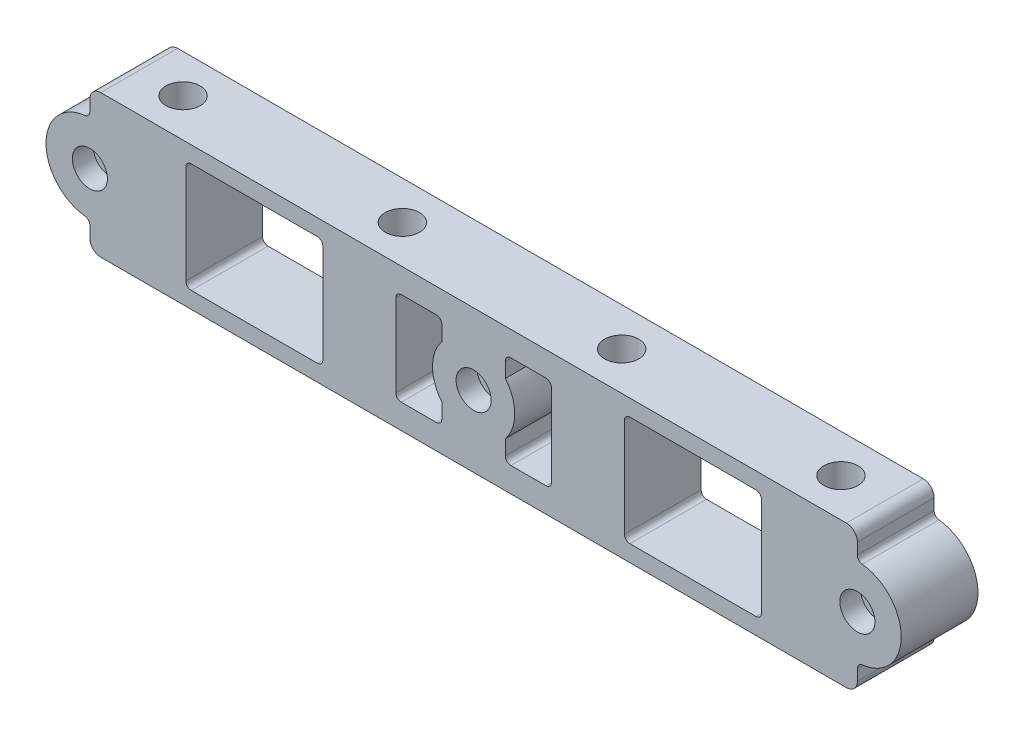
SolidWorks part; units mm, degrees
material "6061-T6 (SS)"
ref_plane "X-Y Datum" through (0, 0, 0) normal (0, 0, 1) x (1, 0, 0)
ref_plane "X-Z Datum" through (0, 0, 0) normal (0, 1, 0) x (1, 0, 0)
ref_plane "Y-Z Datum" through (0, 0, 0) normal (1, 0, 0) x (0, 0, -1)
other "Graphic1"
other "Graphic (Closed) -1"
other "Graphic2"
other "Graphic (Closed) -2"
other "Graphic3"
other "Graphic (Closed) -3"
sketch "Sketch1" plane through (0, 0, 0) normal (0, 1, 0) x (1, 0, 0)
  line L0 (101.6, 8.89) -> (76.2, 8.89) construction
  line L1 (101.6, 17.78) -> (-101.6, 17.78)
  line L2 (101.6, 17.78) -> (101.6, 0)
  line L3 (101.6, 0) -> (-101.6, 0)
  line L4 (-101.6, 17.78) -> (-101.6, 0)
  line L7 (76.2, 8.89) -> (25.4, 8.89) construction
  line L8 (25.4, 8.89) -> (-25.4, 8.89) construction
  line L9 (-25.4, 8.89) -> (-76.2, 8.89) construction
  line L10 (-76.2, 8.89) -> (-101.6, 8.89) construction
  circle A0 centre (76.2, 8.89) radius 3.9688
  circle A1 centre (25.4, 8.89) radius 3.9687
  circle A2 centre (-25.4, 8.89) radius 3.9687
  circle A3 centre (-76.2, 8.89) radius 3.9688
  point P0 (0, 0)
  point P19 (0, 8.89)
  dimension "D3" = 7.9375
  dimension "D1" = 203.2
  dimension "D2" = 17.78
  dimension "D4" = 50.8
  dimension "D5" = 25.4
extrude "Boss-Extrude1" add sketch "Sketch1" against normal blind 33.02
sketch "Sketch2" plane through (0, 0, 0) normal (0, 0, 1) x (1, 0, 0)
  line L0 (80.1687, 0) -> (80.1687, -33.02) construction
  line L1 (-101.6, 0) -> (101.6, 0) construction
  line L2 (-101.6, -33.02) -> (101.6, -33.02) construction
  line L3 (72.2312, 0) -> (72.2312, -33.02) construction
  line L4 (-72.2313, 0) -> (-72.2313, -33.02) construction
  line L5 (-80.1687, 0) -> (-80.1687, -33.02) construction
  line L6 (80.1687, 0) -> (72.2312, 0) construction
  line L7 (80.1687, 0) -> (72.2312, 0) construction
  line L8 (-72.2313, 0) -> (-80.1687, 0) construction
  line L9 (-72.2312, 0) -> (-80.1688, 0) construction
  line L10 (80.1687, -16.51) -> (72.2312, -16.51) construction
  line L11 (-72.2313, -16.51) -> (-80.1687, -16.51) construction
  line L12 (-101.6, -33.02) -> (-101.6, 0) construction
  circle A0 centre (88.9, -16.51) radius 2.4892
  circle A1 centre (0, -16.51) radius 2.4892
  circle A2 centre (-88.9, -16.51) radius 2.4892
  point P12 (76.2, 0)
  point P15 (-76.2, 0)
  point P26 (76.2, -16.51)
  point P27 (-76.2, -16.51)
  point P37 (-101.6, -16.51)
  dimension "D3" = 4.9784
  dimension "D1" = 7.9375
  dimension "D2" = 7.9375
  dimension "D4" = 12.7
  dimension "D5" = 12.7
extrude "Cut-Extrude1" cut sketch "Sketch2" against normal up to surface (17.78 mm away) up to face at (0, -16.51, -17.78)
sketch "Sketch3" plane through (0, 0, 0) normal (0, 0, 1) x (1, 0, 0)
  circle A0 centre (88.9, -16.51) radius 4.064
  circle A1 centre (0, -16.51) radius 4.064
  circle A2 centre (-88.9, -16.51) radius 4.064
  dimension "D1" = 8.128
extrude "Cut-Extrude2" cut sketch "Sketch3" against normal blind 4.826
ref_plane "Plane1" through (0, -16.51, 0) normal (0, 1, 0) x (1, 0, 0)
ref_plane "Plane2" through (0, -16.51, 0) normal (0, 1, 0) x (1, 0, 0)
ref_point "Point1"
ref_point "Point2"
ref_point "Point3"
ref_point "Point4"
sketch "Sketch4" plane through (0, 0, 0) normal (0, 0, 1) x (1, 0, 0)
  line L0 (0, 0) -> (0, -33.02) construction
  line L1 (-36.195, -29.21) -> (-65.405, -29.21)
  line L2 (-34.925, -27.94) -> (-34.925, -5.08)
  line L3 (-36.195, -3.81) -> (-65.405, -3.81)
  line L4 (-66.675, -27.94) -> (-66.675, -5.08)
  line L5 (-8.636, -27.305) -> (-16.764, -27.305)
  line L6 (-7.366, -26.035) -> (-7.366, -22.5488)
  line L7 (-8.636, -5.715) -> (-16.764, -5.715)
  line L8 (-18.034, -26.035) -> (-18.034, -6.985)
  line L9 (-101.6, -33.02) -> (101.6, -33.02) construction
  line L10 (0, -16.51) -> (-101.6, -16.51) construction
  line L11 (-101.6, -33.02) -> (-101.6, 0) construction
  line L12 (-7.366, -10.4712) -> (-7.366, -6.985)
  line L13 (36.195, -3.81) -> (65.405, -3.81)
  line L14 (66.675, -27.94) -> (66.675, -5.08)
  line L15 (36.195, -29.21) -> (65.405, -29.21)
  line L16 (34.925, -27.94) -> (34.925, -5.08)
  line L17 (7.366, -26.035) -> (7.366, -22.5488)
  line L18 (8.636, -27.305) -> (16.764, -27.305)
  line L19 (18.034, -26.035) -> (18.034, -6.985)
  line L20 (8.636, -5.715) -> (16.764, -5.715)
  line L21 (7.366, -10.4712) -> (7.366, -6.985)
  arc A0 (-7.366, -22.5488) -> (-7.366, -10.4712) centre (0, -16.51) cw
  arc A1 (-66.675, -27.94) -> (-65.405, -29.21) centre (-65.405, -27.94) ccw
  arc A2 (-66.675, -5.08) -> (-65.405, -3.81) centre (-65.405, -5.08) cw
  arc A3 (-36.195, -3.81) -> (-34.925, -5.08) centre (-36.195, -5.08) cw
  arc A4 (-34.925, -27.94) -> (-36.195, -29.21) centre (-36.195, -27.94) cw
  arc A5 (-18.034, -6.985) -> (-16.764, -5.715) centre (-16.764, -6.985) cw
  arc A6 (-18.034, -26.035) -> (-16.764, -27.305) centre (-16.764, -26.035) ccw
  arc A7 (-8.636, -5.715) -> (-7.366, -6.985) centre (-8.636, -6.985) cw
  arc A8 (-8.636, -27.305) -> (-7.366, -26.035) centre (-8.636, -26.035) ccw
  arc A9 (66.675, -5.08) -> (65.405, -3.81) centre (65.405, -5.08) ccw
  arc A10 (66.675, -27.94) -> (65.405, -29.21) centre (65.405, -27.94) cw
  arc A11 (36.195, -3.81) -> (34.925, -5.08) centre (36.195, -5.08) ccw
  arc A12 (34.925, -27.94) -> (36.195, -29.21) centre (36.195, -27.94) ccw
  arc A13 (7.366, -22.5488) -> (7.366, -10.4712) centre (0, -16.51) ccw
  arc A14 (8.636, -27.305) -> (7.366, -26.035) centre (8.636, -26.035) cw
  arc A15 (18.034, -26.035) -> (16.764, -27.305) centre (16.764, -26.035) cw
  arc A16 (18.034, -6.985) -> (16.764, -5.715) centre (16.764, -6.985) ccw
  arc A17 (8.636, -5.715) -> (7.366, -6.985) centre (8.636, -6.985) ccw
  point P4 (-50.8, -29.21)
  point P13 (-34.925, -16.51)
  point P19 (-12.7, -27.305)
  point P25 (-66.675, -29.21)
  point P28 (-66.675, -3.81)
  point P33 (-34.925, -29.21)
  point P36 (-18.034, -5.715)
  point P39 (-18.034, -27.305)
  point P42 (-7.366, -5.715)
  dimension "D7" = 9.525
  dimension "D8" = 1.27
  dimension "D1" = 31.75
  dimension "D2" = 50.8
  dimension "D3" = 25.4
  dimension "D4" = 12.7
  dimension "D5" = 10.668
  dimension "D6" = 21.59
extrude "Cut-Extrude3" cut sketch "Sketch4" against normal up to surface (17.78 mm away) up to face at (86.4108, -16.51, -17.78)
sketch "Sketch5" plane through (0, 0, 0) normal (0, 0, 1) x (1, 0, 0)
  line L0 (88.9, -33.02) -> (88.9, 0) construction
  line L1 (-101.6, -33.02) -> (101.6, -33.02) construction
  line L2 (88.9, -27.8692) -> (88.9, -33.02)
  line L3 (88.9, -5.1508) -> (88.9, 0)
  line L4 (-101.6, 0) -> (101.6, 0) construction
  line L5 (88.9, -33.02) -> (101.6, -33.02)
  line L6 (101.6, -33.02) -> (101.6, 0)
  line L7 (101.6, 0) -> (88.9, 0)
  line L8 (0, 0) -> (0, -33.02) construction
  line L9 (-88.9, -5.1508) -> (-88.9, 0)
  line L10 (-101.6, 0) -> (-88.9, 0)
  line L11 (-101.6, -33.02) -> (-101.6, 0)
  line L12 (-88.9, -33.02) -> (-101.6, -33.02)
  line L13 (-88.9, -27.8692) -> (-88.9, -33.02)
  arc A1 (90.0289, -26.6071) -> (90.0289, -6.4129) centre (88.9, -16.51) ccw
  arc A2 (88.9, -5.1508) -> (90.0289, -6.4129) centre (90.17, -5.1508) ccw
  arc A3 (88.9, -27.8692) -> (90.0289, -26.6071) centre (90.17, -27.8692) cw
  arc A4 (-88.9, -5.1508) -> (-90.0289, -6.4129) centre (-90.17, -5.1508) cw
  arc A5 (-88.9, -27.8692) -> (-90.0289, -26.6071) centre (-90.17, -27.8692) ccw
  arc A6 (-90.0289, -26.6071) -> (-90.0289, -6.4129) centre (-88.9, -16.51) cw
  point P10 (88.9, -16.51)
  point P19 (88.9, -26.67)
  dimension "D2" = 1.27
  dimension "D1" = 6.35
extrude "Cut-Extrude4" cut sketch "Sketch5" against normal up to surface (17.78 mm away) up to face at (11.8491, -16.51, -17.78)
fillet "Fillet1" radius 2.54 4 edges at (88.9, -33.02, -8.89) (-88.9, -33.02, -8.89) (-88.9, 0, -8.89) (88.9, 0, -8.89)
